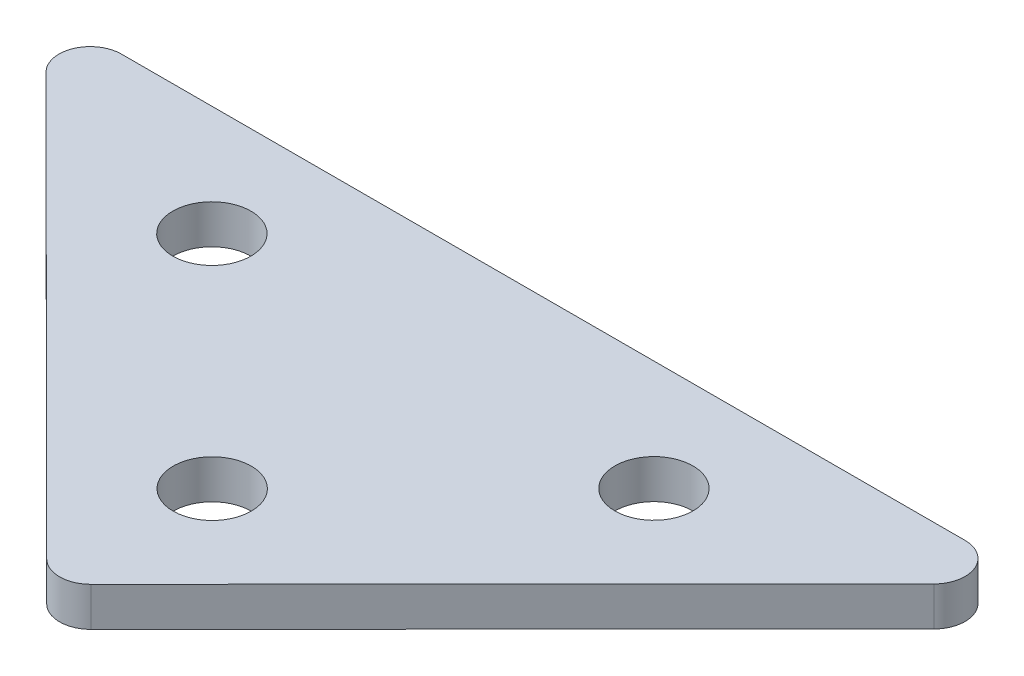
SolidWorks part; units mm, degrees
material "6061 Alloy"
ref_plane "Front Plane" through (0, 0, 0) normal (0, 0, 1) x (1, 0, 0)
ref_plane "Top Plane" through (0, 0, 0) normal (0, 1, 0) x (1, 0, 0)
ref_plane "Right Plane" through (0, 0, 0) normal (1, 0, 0) x (0, 0, -1)
sketch "Outline" plane through (0, 94.6334, 0) normal (0, 1, 0) x (1, 0, 0)
  line L0 (175.9688, -346.3969) -> (173.7219, -344.1536)
  line L1 (173.7219, -344.1536) -> (175.9652, -341.9068)
  line L2 (173.7219, -344.1536) -> (658.2715, 141.1641) construction
  line L3 (177.7598, -340.1093) -> (212.0117, -305.8031)
  line L4 (174.1677, -340.1122) -> (139.8615, -305.8603)
  line L5 (-325.5841, 158.8488) -> (159.7336, -325.7009) construction
  line L12 (141.6542, -301.5228) -> (210.2122, -301.4685)
  arc A0 (139.8615, -305.8603) -> (141.6542, -301.5228) centre (141.6562, -304.0628) cw
  arc A1 (174.1677, -340.1122) -> (177.7598, -340.1093) centre (175.9624, -338.3147) ccw
  arc A2 (212.0117, -305.8031) -> (210.2122, -301.4685) centre (210.2143, -304.0085) ccw
  point P25 (135.5221, -301.5277)
  point P31 (216.3443, -301.4636)
  dimension "D1" = 2.54
  dimension "D2" = 2.54
  dimension "D3" = 2.54
extrude "Boss-Extrude1" add sketch "Outline" along normal blind 3.175 contours L12 A2 L3 A1 L4 A0
sketch "Hole locations" plane through (0, 97.8084, 0) normal (0, 1, 0) x (1, 0, 0)
  line L0 (166.9814, -337.4238) -> (175.9545, -328.4364)
  line L1 (166.9814, -337.4238) -> (211.8471, -292.4869) construction
  line L2 (175.9545, -328.4364) -> (193.9008, -310.4617)
  line L3 (140.0051, -292.5438) -> (157.9798, -310.4901)
  line L4 (166.4635, -318.9603) -> (140.0051, -292.5438) construction
hole_wizard "1/4 (0.25) Diameter Hole1" positions "Sketch6" profile "Sketch7" hole size "1/4" standard "ANSI Inch" end condition through all
sketch "Sketch6" plane through (0, 97.8084, 0) normal (0, 1, 0) x (1, 0, 0)
  point P0 (157.9798, -310.4901)
  point P3 (175.9545, -328.4364)
  point P6 (193.9008, -310.4617)
sketch "Sketch7" plane through (157.9798, 97.8084, 310.4901) normal (1, 0, 0) x (0, 0, 1)
  line L0 (0, 0) -> (0, 3.175)
  line L1 (0, 3.175) -> (3.175, 3.175)
  line L2 (3.175, 3.175) -> (3.175, 0)
  line L5 (3.175, 0) -> (0, 0)
  line L11 (0, -6.35) -> (0, 107.95) construction
  dimension "Thru Hole Dia." = 6.35
  dimension "Thru Hole Depth" = 3.175
